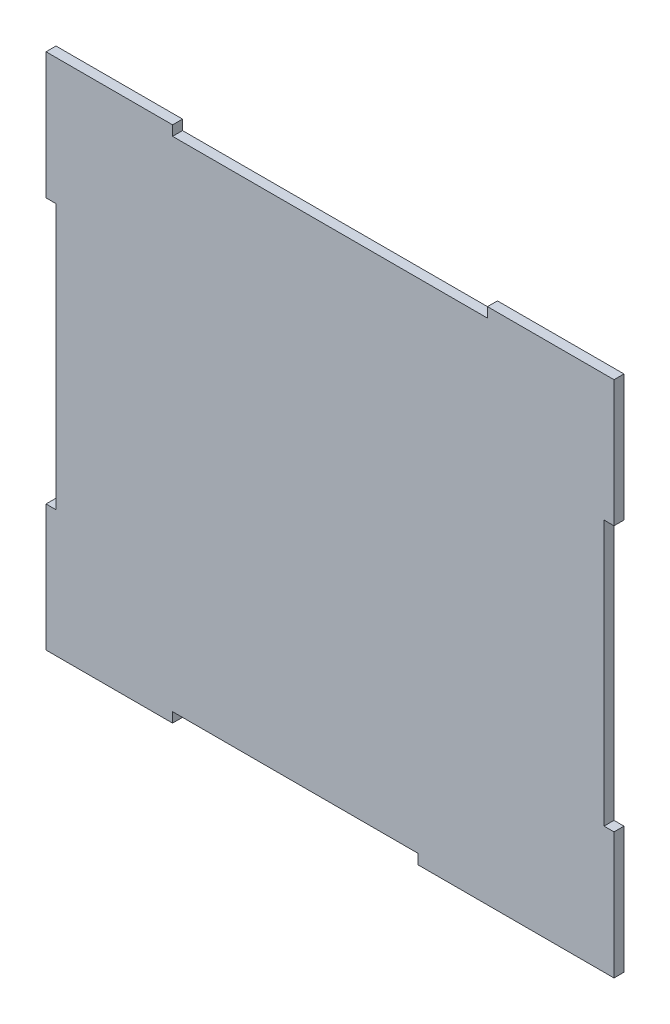
SolidWorks part; units mm, degrees
ref_plane "Front Plane" through (0, 0, 0) normal (0, 0, 1) x (1, 0, 0)
ref_plane "Top Plane" through (0, 0, 0) normal (0, 1, 0) x (1, 0, 0)
ref_plane "Right Plane" through (0, 0, 0) normal (1, 0, 0) x (0, 0, -1)
sketch "Sketch1" plane through (0, 0, 0) normal (0, 0, 1) x (1, 0, 0)
  line L0 (-52, 52) -> (-26.6, 52)
  line L5 (-26.6, -50) -> (22.63, -50)
  line L6 (-50, -26.6) -> (-50, 26.6)
  line L7 (-26.6, 50) -> (36.6, 50)
  line L8 (60, -26.6) -> (60, 26.6)
  line L9 (-52, 26.6) -> (-52, 52)
  line L11 (62, -52) -> (62, -26.6)
  line L12 (-52, -52) -> (-26.6, -52)
  line L13 (-52, -52) -> (-52, -26.6)
  line L14 (-26.6, 50) -> (-26.6, 52)
  line L15 (36.6, 52) -> (36.6, 50)
  line L16 (36.6, 52) -> (62, 52)
  line L17 (-52, 52) -> (62, 52) construction
  line L18 (60, 26.6) -> (62, 26.6)
  line L19 (60, -26.6) -> (62, -26.6)
  line L20 (-52, -26.6) -> (-50, -26.6)
  line L21 (-52, 26.6) -> (-50, 26.6)
  line L22 (-26.6, -50) -> (-26.6, -52)
  line L23 (22.63, -52) -> (22.63, -50)
  line L24 (-50, 50) -> (60, 50) construction
  line L25 (-50, -50) -> (-50, 50) construction
  line L26 (60, -50) -> (60, 50) construction
  line L27 (-50, -50) -> (60, -50) construction
  line L28 (-52, -52) -> (-52, 52) construction
  line L29 (62, 26.6) -> (62, 52)
  line L30 (62, -52) -> (62, 52) construction
  line L31 (22.63, -52) -> (62, -52)
  line L32 (-52, -52) -> (62, -52) construction
  dimension "D2" = 110
  dimension "D3" = 25.4
  dimension "D4" = 25.4
  dimension "D5" = 39.37
  dimension "D6" = 25.4
  dimension "D7" = 25.4
  dimension "D8" = 25.4
  dimension "D9" = 25.4
  dimension "D10" = 25.4
extrude "Boss-Extrude1" add sketch "Sketch1" along normal blind 2
